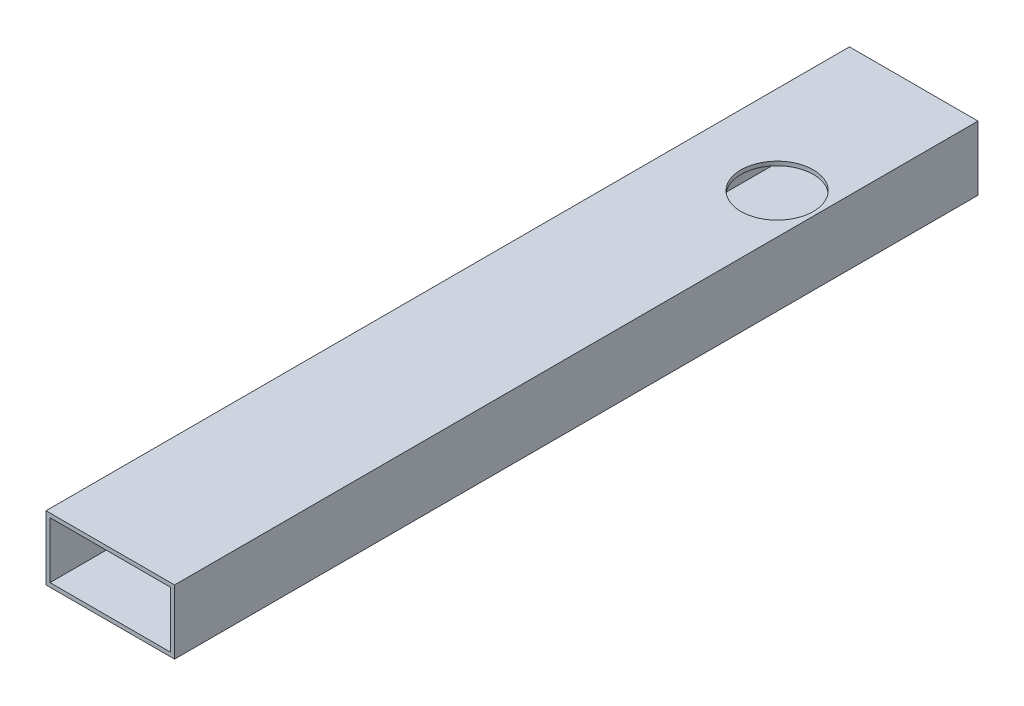
SolidWorks part; units mm, degrees
material "6061 Alloy"
ref_plane "Front Plane" through (0, 0, 0) normal (0, 0, 1) x (1, 0, 0)
ref_plane "Top Plane" through (0, 0, 0) normal (0, 1, 0) x (1, 0, 0)
ref_plane "Right Plane" through (0, 0, 0) normal (1, 0, 0) x (0, 0, -1)
sketch "Sketch1" plane through (0, 0, 0) normal (0, 0, 1) x (1, 0, 0)
  line L0 (-23.8125, 11.1125) -> (23.8125, 11.1125)
  line L2 (-25.4, 12.7) -> (25.4, 12.7)
  line L3 (-25.4, 12.7) -> (-25.4, -12.7)
  line L4 (-25.4, -12.7) -> (25.4, -12.7)
  line L5 (25.4, 12.7) -> (25.4, -12.7)
  line L10 (23.8125, 11.1125) -> (23.8125, -11.1125)
  line L11 (-23.8125, -11.1125) -> (23.8125, -11.1125)
  line L12 (-23.8125, 11.1125) -> (-23.8125, -11.1125)
  point P12 (0, 12.7)
  point P14 (25.4, 0)
  dimension "Wall Thickness" = 1.5875
  dimension "Outside Width" = 50.8
  dimension "Outside Height" = 25.4
  dimension "Inside Height" = 22.225
  dimension "Inside Width" = 47.625
sketch "Sketch2" plane through (0, 0, 0) normal (1, 0, 0) x (0, 0, -1)
  line L0 (158.75, 0) -> (-158.75, 0)
  point P4 (0, 0)
  point P7 (-158.75, 0)
  point P10 (158.75, 0)
  dimension "Length" = 317.5
sketch "Sketch3" plane through (0, 0, 0) normal (0, 0, 1) x (1, 0, 0)
  line L21 (25.4, 12.7) -> (-25.4, 12.7)
  line L22 (25.4, -12.7) -> (25.4, 12.7)
  line L23 (-25.4, -12.7) -> (25.4, -12.7)
  line L24 (-25.4, 12.7) -> (-25.4, -12.7)
  line L25 (25.4, 12.7) -> (-25.4, 12.7)
  line L26 (25.4, -12.7) -> (25.4, 12.7)
  line L27 (-25.4, -12.7) -> (25.4, -12.7)
  line L28 (-25.4, 12.7) -> (-25.4, -12.7)
  line L29 (23.8125, 11.1125) -> (-23.8125, 11.1125)
  line L30 (23.8125, -11.1125) -> (23.8125, 11.1125)
  line L31 (-23.8125, -11.1125) -> (23.8125, -11.1125)
  line L32 (-23.8125, 11.1125) -> (-23.8125, -11.1125)
  line L33 (23.8125, 11.1125) -> (-23.8125, 11.1125)
  line L34 (23.8125, -11.1125) -> (23.8125, 11.1125)
  line L35 (-23.8125, -11.1125) -> (23.8125, -11.1125)
  line L36 (-23.8125, 11.1125) -> (-23.8125, -11.1125)
  dimension "D1" = 0
  dimension "D2" = 0
extrude "Boss-Extrude1" add sketch "Sketch3" along normal up to vertex (158.75 mm away) and the other way up to vertex (158.75 mm away) up to point (0, 0, 158.75) other way up to point (0, 0, -158.75)
sketch "Drawing Reference" plane through (0, 0, 0) normal (1, 0, 0) x (0, 0, -1)
  line L0 (-158.75, 0) -> (158.75, 0) construction
  line L1 (0, -12.7) -> (0, 12.7) construction
  line L2 (-158.75, -12.7) -> (158.75, -12.7) construction
  line L5 (-158.75, 12.7) -> (158.75, 12.7) construction
  point P7 (-122.174, 0)
  point P8 (122.174, 0)
  dimension "D1" = 36.576
sketch "Sketch4" plane through (0, 12.7, 0) normal (0, 1, 0) x (1, 0, 0)
  line L0 (0, 158.75) -> (0, 95.25) construction
  line L1 (25.4, 158.75) -> (-25.4, 158.75) construction
  line L2 (0, 95.25) -> (9.525, 95.25) construction
  line L3 (0, 158.75) -> (0, -26.67) construction
  circle A1 centre (9.525, 95.25) radius 14.2875
  circle A3 centre (9.525, 95.25) radius 117.5004 construction
  dimension "D1" = 63.5
  dimension "D3" = 235.0008
  dimension "D2" = 9.525
extrude "Cut-Extrude1" cut sketch "Sketch4" against normal blind 39.37
equation "\"D1@Drawing Reference\"=\"Outside Width@Sketch1\" * 0.72"
